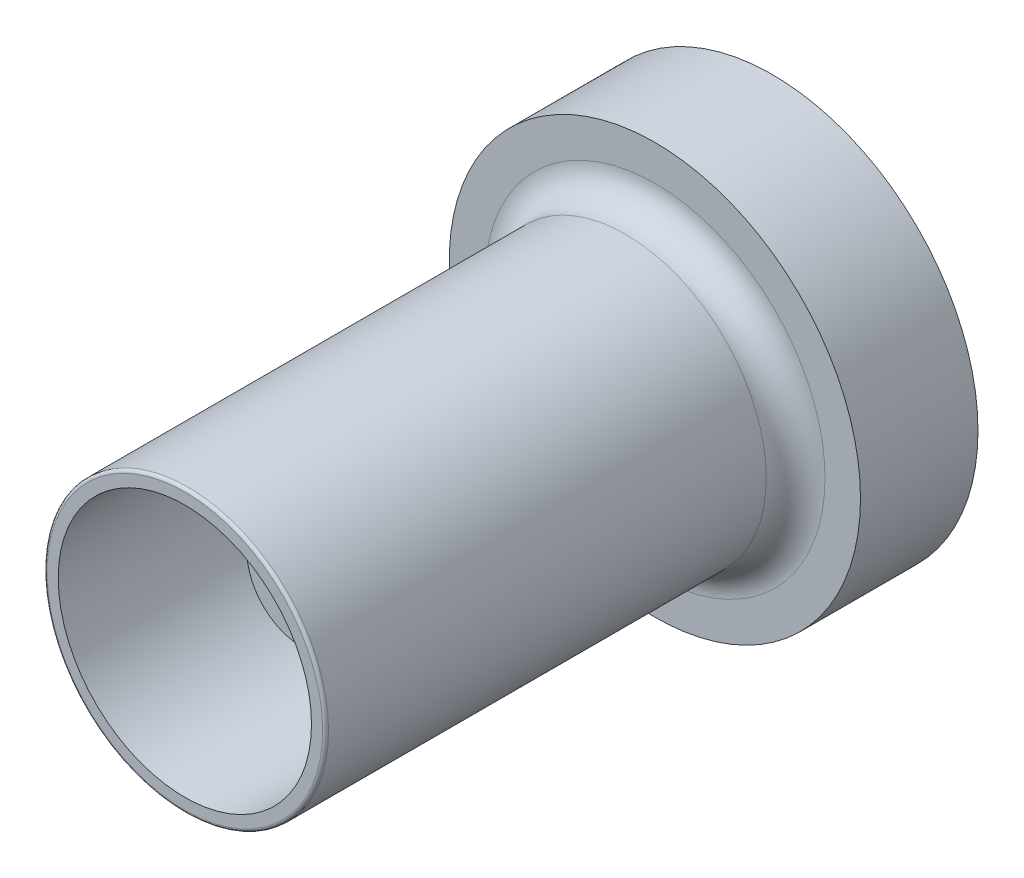
SolidWorks part; units mm, degrees
material "201 Annealed Stainless Steel (SS)"
ref_plane "Front Plane" through (0, 0, 0) normal (0, 0, 1) x (1, 0, 0)
ref_plane "Top Plane" through (0, 0, 0) normal (0, 1, 0) x (1, 0, 0)
ref_plane "Right Plane" through (0, 0, 0) normal (1, 0, 0) x (0, 0, -1)
sketch "Sketch1" plane through (0, 0, 0) normal (0, 0, 1) x (1, 0, 0)
  circle A0 centre (0, 0) radius 7
extrude "Boss-Extrude1" add sketch "Sketch1" along normal blind 4
sketch "Sketch2" plane through (0, 0, 4) normal (0, 0, 1) x (1, 0, 0)
  circle A0 centre (0, 0) radius 4.7913
extrude "Boss-Extrude2" add sketch "Sketch2" along normal blind 16
sketch "Sketch3" plane through (0, 0, 20) normal (0, 0, 1) x (1, 0, 0)
  circle A0 centre (0, 0) radius 4.3104
extrude "Cut-Extrude1" cut sketch "Sketch3" against normal blind 16
sketch "Sketch4" plane through (0, 0, 4) normal (0, 0, 1) x (1, 0, 0)
  circle A0 centre (0, 0) radius 1.1911
  circle A1 centre (0, 0) radius 1.8891
extrude "Boss-Extrude3" add sketch "Sketch4" along normal blind 12
fillet "Fillet1" radius 1 1 edges at (4.7913, 0, 4)
fillet "Fillet2" radius 0.1 1 edges at (4.7913, 0, 20)
